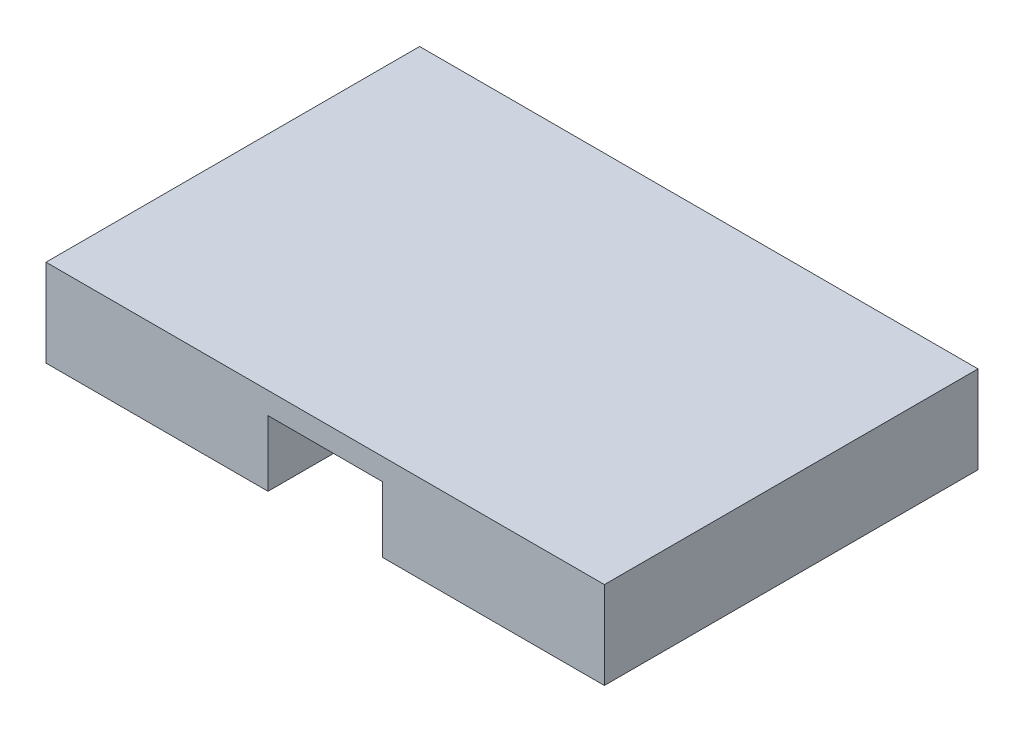
SolidWorks part; units mm, degrees
ref_plane "Front Plane" through (0, 0, 0) normal (0, 0, 1) x (1, 0, 0)
ref_plane "Top Plane" through (0, 0, 0) normal (0, 1, 0) x (1, 0, 0)
ref_plane "Right Plane" through (0, 0, 0) normal (1, 0, 0) x (0, 0, -1)
sketch "Sketch1" plane through (0, 0, 0) normal (0, 1, 0) x (1, 0, 0)
  line L1 (0, 0) -> (127.76, 0)
  line L2 (0, 0) -> (0, 85.48)
  line L3 (0, 85.48) -> (127.76, 85.48)
  line L4 (127.76, 0) -> (127.76, 85.48)
  dimension "D1" = 85.48
  dimension "D2" = 127.76
extrude "Boss-Extrude1" add sketch "Sketch1" along normal blind 20
sketch "Sketch2" plane through (0, 20, 0) normal (0, 1, 0) x (1, 0, 0)
  line L0 (127.76, 85.48) -> (0, 85.48) construction
  line L1 (0, 85.48) -> (50.8, 85.48)
  line L2 (0, 85.48) -> (0, 0)
  line L3 (0, 0) -> (50.8, 0)
  line L4 (50.8, 85.48) -> (50.8, 0)
  line L5 (127.76, 0) -> (76.96, 0)
  line L6 (127.76, 0) -> (127.76, 85.48)
  line L7 (127.76, 85.48) -> (76.96, 85.48)
  line L8 (76.96, 0) -> (76.96, 85.48)
  line L9 (0, 85.48) -> (12.7, 85.48)
  line L10 (0, 85.48) -> (0, 72.78)
  line L13 (50.8, 0) -> (38.1, 0)
  line L14 (50.8, 0) -> (50.8, 12.7)
  line L17 (76.96, 85.48) -> (89.66, 85.48)
  line L18 (76.96, 85.48) -> (76.96, 72.78)
  line L21 (127.76, 0) -> (115.06, 0)
  line L22 (127.76, 0) -> (127.76, 12.7)
  line L26 (50.8, 85.48) -> (76.96, 85.48)
  line L27 (50.8, 85.48) -> (50.8, 0)
  line L28 (50.8, 0) -> (76.96, 0)
  line L29 (76.96, 85.48) -> (76.96, 0)
  line M30 (0, 0) -> (127.76, 0)
  line M32 (127.76, 85.48) -> (0, 85.48)
  dimension "D1" = 50.8
extrude "Cut-Extrude1" cut sketch "Sketch2" against normal blind 20 from offset 5 contours L8 L4 M30 M32 offset against normal yes
